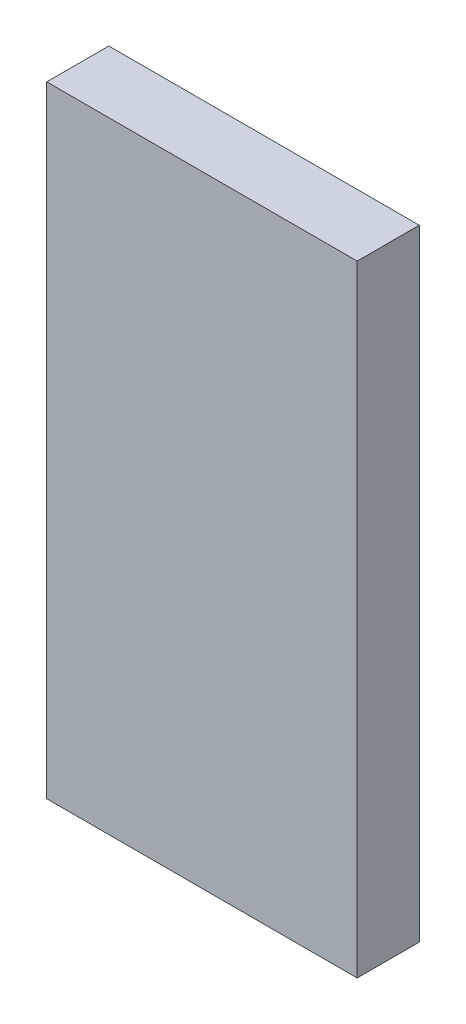
SolidWorks part; units mm, degrees
ref_plane "Front Plane" through (0, 0, 0) normal (0, 0, 1) x (1, 0, 0)
ref_plane "Top Plane" through (0, 0, 0) normal (0, 1, 0) x (1, 0, 0)
ref_plane "Right Plane" through (0, 0, 0) normal (1, 0, 0) x (0, 0, -1)
sketch "Sketch2" plane through (0, 0, 0) normal (0, 0, 1) x (1, 0, 0)
  line L1 (-30, -60) -> (30, -60)
  line L2 (-30, -60) -> (-30, 60)
  line L3 (-30, 60) -> (30, 60)
  line L4 (30, -60) -> (30, 60)
  line L5 (-30, -60) -> (30, 60) construction
  line L6 (-30, 60) -> (30, -60) construction
  point P0 (0, 0)
  dimension "D1" = 120
  dimension "D2" = 60
extrude "Boss-Extrude1" add sketch "Sketch2" along normal mid plane 12
